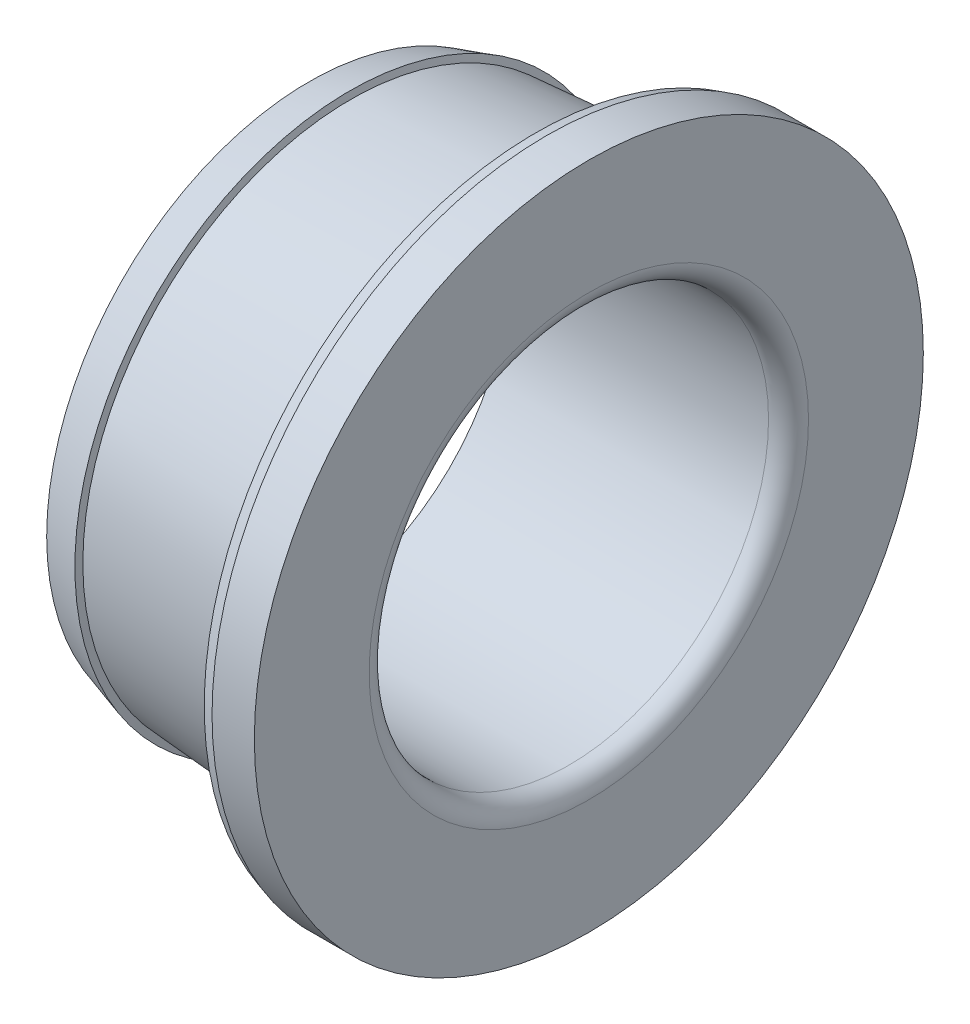
SolidWorks part; units mm, degrees
material "SUJ2"
ref_plane "Front Plane" through (0, 0, 0) normal (0, 0, 1) x (1, 0, 0)
ref_plane "Top Plane" through (0, 0, 0) normal (0, 1, 0) x (1, 0, 0)
ref_plane "Right Plane" through (0, 0, 0) normal (1, 0, 0) x (0, 0, -1)
sketch "ｽｹｯﾁ1" plane through (0, 0, 0) normal (0, 0, 1) x (1, 0, 0)
  line L0 (1.25, 13.149) -> (1.25, 10)
  line L1 (1.25, 10) -> (14.25, 10)
  line L2 (15.25, 11) -> (15.25, 16.75)
  line L3 (15.25, 16.75) -> (13.131, 16.75)
  line L4 (13.131, 16.75) -> (12.5703, 16.58)
  line L5 (12.5703, 16.58) -> (12.9499, 14.1048)
  line L6 (12.9499, 14.1048) -> (3.3294, 13.4181)
  line L7 (3.3294, 13.4181) -> (3.2764, 13.7632)
  line L8 (3.2764, 13.7632) -> (1.25, 13.149)
  line L9 (1.25, 0) -> (15.2513, 0) construction
  arc A0 (14.25, 10) -> (15.25, 11) centre (14.25, 11) ccw
revolve "回転1" add sketch "ｽｹｯﾁ1" angle 360 about L9
